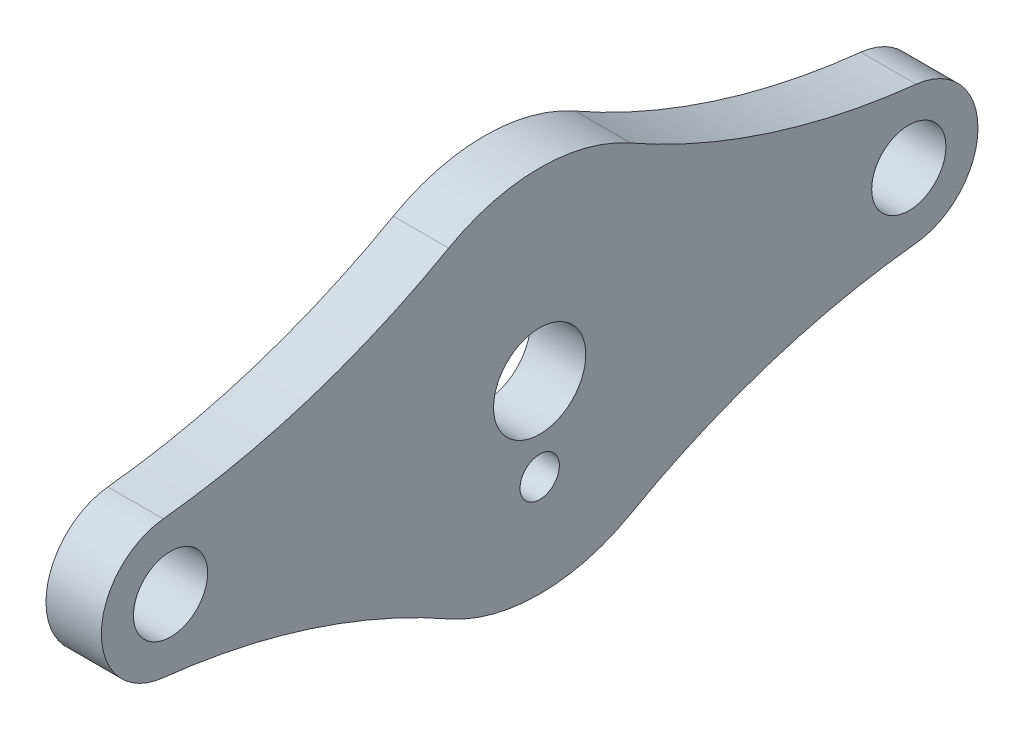
SolidWorks part; units mm, degrees
material "PET"
ref_plane "Front" through (0, 0, 0) normal (0, 0, 1) x (1, 0, 0)
ref_plane "Top" through (0, 0, 0) normal (0, 1, 0) x (1, 0, 0)
ref_plane "Right" through (0, 0, 0) normal (1, 0, 0) x (0, 0, -1)
sketch "Sketch1" plane through (0, 0, 0) normal (1, 0, 0) x (0, 0, -1)
  line L0 (0, 0) -> (0, 5.645) construction
  arc A0 (-25.906, 4.7355) -> (-25.906, -4.7355) centre (-25.4, 0) ccw
  circle A2 centre (0, 0) radius 25.4 construction
  arc A3 (-6.2607, -11.0496) -> (6.2607, -11.0496) centre (0, 0) ccw
  arc A4 (-25.906, 4.7355) -> (-6.2607, 11.0496) centre (-31.3035, 55.248) ccw
  arc A5 (-25.906, -4.7355) -> (-6.2607, -11.0496) centre (-31.3035, -55.248) cw
  arc A6 (25.906, -4.7355) -> (6.2607, -11.0496) centre (31.3035, -55.248) ccw
  arc A7 (25.906, 4.7355) -> (6.2607, 11.0496) centre (31.3035, 55.248) cw
  arc A8 (25.906, 4.7355) -> (25.906, -4.7355) centre (25.4, 0) cw
  arc A9 (6.2607, 11.0496) -> (-6.2607, 11.0496) centre (0, 0) ccw
  point P18 (-25.906, -4.7355)
  point P19 (-6.2607, -11.0496)
  dimension "D1" = 50.8
  dimension "D2" = 9.525
  dimension "D3" = 25.4
  dimension "D4" = 50.8
extrude "Boss-Extrude1" add sketch "Sketch1" against normal blind 3.81
hole_wizard "#10 Clearance Hole1" positions "Sketch2" profile "Sketch3" hole size "#10" standard "ANSI Inch" end condition through all
sketch "Sketch2" plane through (-3.81, 0, 0) normal (-1, 0, 0) x (0, 0, 1)
  point P0 (-25.4, 0)
  point P3 (25.4, 0)
sketch "Sketch3" plane through (-3.81, 0, -25.4) normal (0, 1, 0) x (0, 0, 1)
  line L0 (0, 0) -> (0, 3.81)
  line L1 (0, 3.81) -> (2.5527, 3.81)
  line L2 (2.5527, 3.81) -> (2.5527, 0)
  line L5 (2.5527, 0) -> (0, 0)
  line L11 (0, -6.35) -> (0, 107.95) construction
  dimension "Thru Hole Dia." = 5.1054
  dimension "Thru Hole Depth" = 3.81
hole_wizard "#6-32 Tapped Hole1" positions "Sketch5" profile "Sketch6" tap size "#6-32" standard "ANSI Inch" end condition through all
sketch "Sketch5" plane through (-3.81, 0, 0) normal (-1, 0, 0) x (0, 0, 1)
  point P0 (0, -5.715)
  point P4 (0, 0)
  dimension "D1" = 5.715
sketch "Sketch6" plane through (-3.81, -5.715, 0) normal (0, 1, 0) x (0, 0, 1)
  line L0 (0, 0) -> (0, 3.81)
  line L1 (0, 3.81) -> (1.3525, 3.81)
  line L2 (1.3525, 3.81) -> (1.3525, 0)
  line L5 (1.3525, 0) -> (0, 0)
  line L11 (0, -6.35) -> (0, 107.95) construction
  dimension "Thru Tap Drill Dia." = 2.7051
  dimension "Thru Tap Drill Depth" = 3.81
cosmetic thread "Hole Thread1" parameters "D2"=3.5052
sketch "Sketch4" plane through (-3.81, 0, 0) normal (-1, 0, 0) x (0, 0, 1)
  circle A0 centre (0, 0) radius 3.175
  dimension "D1" = 6.35
extrude "Cut-Extrude1" cut sketch "Sketch4" against normal through all
